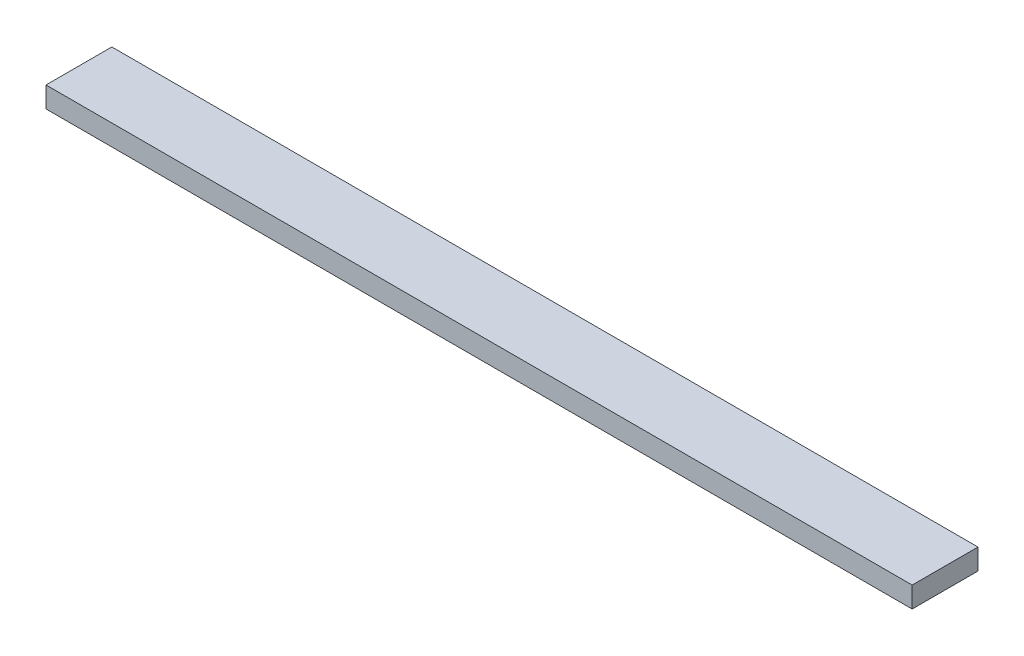
SolidWorks part; units mm, degrees
ref_plane "Front Plane" through (0, 0, 0) normal (0, 0, 1) x (1, 0, 0)
ref_plane "Top Plane" through (0, 0, 0) normal (0, 1, 0) x (1, 0, 0)
ref_plane "Right Plane" through (0, 0, 0) normal (1, 0, 0) x (0, 0, -1)
sketch "Sketch1" plane through (0, 0, 0) normal (0, 1, 0) x (1, 0, 0)
  line L1 (-691.8296, -43.3638) -> (70.1704, -43.3638)
  line L2 (-691.8296, -43.3638) -> (-691.8296, -101.2758)
  line L3 (-691.8296, -101.2758) -> (70.1704, -101.2758)
  line L4 (70.1704, -43.3638) -> (70.1704, -101.2758)
  dimension "D1" = 762
  dimension "D2" = 57.912
extrude "Boss-Extrude1" add sketch "Sketch1" along normal blind 18.288
